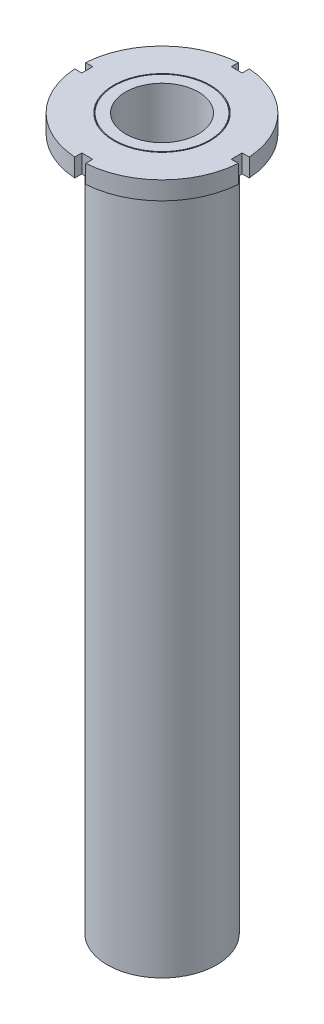
SolidWorks part; units mm, degrees
material "AISI 304"
ref_plane "Front Plane" through (0, 0, 0) normal (0, 0, 1) x (1, 0, 0)
ref_plane "Top Plane" through (0, 0, 0) normal (0, 1, 0) x (1, 0, 0)
ref_plane "Right Plane" through (0, 0, 0) normal (1, 0, 0) x (0, 0, -1)
sketch "Sketch1" plane through (0, 0, 0) normal (0, 1, 0) x (1, 0, 0)
  circle A0 centre (0, 0) radius 15
  dimension "D1" = 30
extrude "Boss-Extrude1" add sketch "Sketch1" along normal blind 190
sketch "Sketch2" plane through (0, 190, 0) normal (0, 1, 0) x (1, 0, 0)
  line L0 (-1.5, 20.5) -> (1.5, 20.5)
  line L1 (0, 20.5) -> (0, -20.5) construction
  line L2 (1.5, 20.5) -> (1.5, 22.4499)
  line L3 (-1.5, 20.5) -> (-1.5, 22.4499)
  line L4 (20.5, 1.5) -> (22.4499, 1.5)
  line L5 (20.5, 1.5) -> (20.5, -1.5)
  line L6 (20.5, -1.5) -> (22.4499, -1.5)
  line L7 (1.5, -20.5) -> (1.5, -22.4499)
  line L8 (1.5, -20.5) -> (-1.5, -20.5)
  line L9 (-1.5, -20.5) -> (-1.5, -22.4499)
  line L10 (-20.5, -1.5) -> (-22.4499, -1.5)
  line L11 (-20.5, -1.5) -> (-20.5, 1.5)
  line L12 (-20.5, 1.5) -> (-22.4499, 1.5)
  arc A0 (-22.4499, -1.5) -> (-1.5, -22.4499) centre (0, 0) ccw
  arc A1 (22.4499, 1.5) -> (1.5, 22.4499) centre (0, 0) ccw
  arc A2 (-1.5, 22.4499) -> (-22.4499, 1.5) centre (0, 0) ccw
  arc A3 (1.5, -22.4499) -> (22.4499, -1.5) centre (0, 0) ccw
  point P6 (0, 0)
  point P9 (0, 20.5)
  point P26 (0, 0)
  dimension "D4" = 1.9499
  dimension "D6" = 3
  dimension "D7" = 1.9499
extrude "Boss-Extrude2" add sketch "Sketch2" along normal blind 5
sketch "Sketch3" plane through (0, 195, 0) normal (0, 1, 0) x (1, 0, 0)
  circle A0 centre (0, 0) radius 13
  circle A1 centre (0, 0) radius 13.25
  dimension "D1" = 26
  dimension "D2" = 26.5
extrude "Cut-Extrude1" cut sketch "Sketch3" against normal blind 0.5
sketch "Sketch4" plane through (0, 195, 0) normal (0, 1, 0) x (1, 0, 0)
  circle A0 centre (0, 0) radius 10
  dimension "D1" = 20
extrude "Cut-Extrude2" cut sketch "Sketch4" against normal through all
sketch "Sketch5" plane through (0, 0, 0) normal (1, 0, 0) x (0, 0, -1)
  line L0 (-1.5, 190) -> (1.5, 190) construction
  circle A0 centre (0, 180) radius 1.5
  dimension "D1" = 3
  dimension "D2" = 10
extrude "Boss-Extrude3" add sketch "Sketch5" along normal mid plane 20.7
sketch "Sketch6" plane through (0, 0, 0) normal (0, -1, 0) x (1, 0, 0)
  point P0 (0, 0)
